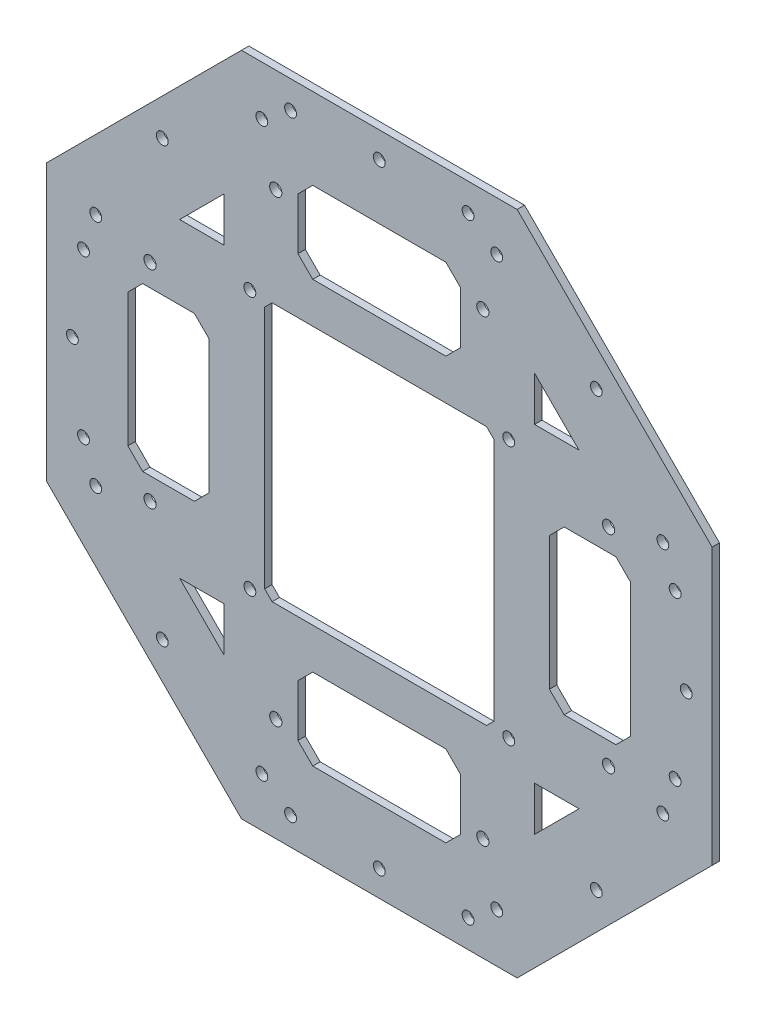
SolidWorks part; units mm, degrees
material "碳纤维板_1600kg_m3"
ref_plane "前视基准面" through (0, 0, 0) normal (0, 0, 1) x (1, 0, 0)
ref_plane "上视基准面" through (0, 0, 0) normal (0, 1, 0) x (1, 0, 0)
ref_plane "右视基准面" through (0, 0, 0) normal (1, 0, 0) x (0, 0, -1)
other "Configuration Table"
sketch "草图1" plane through (0, 0, 0) normal (0, 0, 1) x (1, 0, 0)
  line L0 (90, 37.2792) -> (37.2792, 90)
  line L1 (37.2792, 90) -> (-37.2792, 90)
  line L2 (-37.2792, 90) -> (-90, 37.2792)
  line L3 (-90, 37.2792) -> (-90, -37.2792)
  line L4 (-90, -37.2792) -> (-37.2792, -90)
  line L5 (-37.2792, -90) -> (37.2792, -90)
  line L6 (37.2792, -90) -> (90, -37.2792)
  line L7 (90, -37.2792) -> (90, 37.2792)
  circle A0 centre (83, 0) radius 1.6
  circle A1 centre (76.682, 31.7627) radius 1.6
  circle A2 centre (58.6899, 58.6899) radius 1.6
  circle A3 centre (31.7627, 76.682) radius 1.6
  circle A4 centre (0, 83) radius 1.6
  circle A5 centre (-31.7627, 76.682) radius 1.6
  circle A6 centre (-58.6899, 58.6899) radius 1.6
  circle A7 centre (-76.682, 31.7627) radius 1.6
  circle A8 centre (-83, 0) radius 1.6
  circle A9 centre (-76.682, -31.7627) radius 1.6
  circle A10 centre (-58.6899, -58.6899) radius 1.6
  circle A11 centre (-31.7627, -76.682) radius 1.6
  circle A12 centre (0, -83) radius 1.6
  circle A13 centre (31.7627, -76.682) radius 1.6
  circle A14 centre (58.6899, -58.6899) radius 1.6
  circle A15 centre (76.682, -31.7627) radius 1.6
  circle A16 centre (-35, -35) radius 1.6
  circle A17 centre (-35, 35) radius 1.6
  circle A18 centre (35, -35) radius 1.6
  circle A19 centre (35, 35) radius 1.6
  circle A20 centre (-24, -82.5) radius 1.6
  circle A21 centre (-24, 82.5) radius 1.6
  circle A22 centre (24, -82.5) radius 1.6
  circle A23 centre (24, 82.5) radius 1.6
extrude "正八边形下板_外围16孔_无支脚孔" add sketch "草图1" along normal blind 2
sketch "草图2" plane through (0, 0, 0) normal (0, 0, 1) x (1, 0, 0)
  circle A0 centre (-80, -22) radius 1.6
  circle A1 centre (-80, 22) radius 1.6
  circle A2 centre (80, -22) radius 1.6
  circle A3 centre (80, 22) radius 1.6
extrude "左右摄像头铰链M3孔" cut sketch "草图2" along normal blind 2
sketch "草图3" plane through (0, 0, 0) normal (0, 0, 1) x (1, 0, 0)
  line L0 (24, 9.9411) -> (9.9411, 24)
  line L1 (9.9411, 24) -> (-9.9411, 24)
  line L2 (-9.9411, 24) -> (-24, 9.9411)
  line L3 (-24, 9.9411) -> (-24, -9.9411)
  line L4 (-24, -9.9411) -> (-9.9411, -24)
  line L5 (-9.9411, -24) -> (9.9411, -24)
  line L6 (9.9411, -24) -> (24, -9.9411)
  line L7 (24, -9.9411) -> (24, 9.9411)
  line L8 (-18, 46) -> (18, 46)
  line L9 (18, 46) -> (22, 50)
  line L10 (22, 50) -> (22, 64)
  line L11 (22, 64) -> (18, 68)
  line L12 (18, 68) -> (-18, 68)
  line L13 (-18, 68) -> (-22, 64)
  line L14 (-22, 64) -> (-22, 50)
  line L15 (-22, 50) -> (-18, 46)
  line L16 (-46, -18) -> (-46, 18)
  line L17 (-46, 18) -> (-50, 22)
  line L18 (-50, 22) -> (-64, 22)
  line L19 (-64, 22) -> (-68, 18)
  line L20 (-68, 18) -> (-68, -18)
  line L21 (-68, -18) -> (-64, -22)
  line L22 (-64, -22) -> (-50, -22)
  line L23 (-50, -22) -> (-46, -18)
  line L24 (18, -46) -> (-18, -46)
  line L25 (-18, -46) -> (-22, -50)
  line L26 (-22, -50) -> (-22, -64)
  line L27 (-22, -64) -> (-18, -68)
  line L28 (-18, -68) -> (18, -68)
  line L29 (18, -68) -> (22, -64)
  line L30 (22, -64) -> (22, -50)
  line L31 (22, -50) -> (18, -46)
  line L32 (46, 18) -> (46, -18)
  line L33 (46, -18) -> (50, -22)
  line L34 (50, -22) -> (64, -22)
  line L35 (64, -22) -> (68, -18)
  line L36 (68, -18) -> (68, 18)
  line L37 (68, 18) -> (64, 22)
  line L38 (64, 22) -> (50, 22)
  line L39 (50, 22) -> (46, 18)
  line L40 (-42, -42) -> (-54, -42)
  line L41 (-54, -42) -> (-42, -54)
  line L42 (-42, -54) -> (-42, -42)
  line L43 (-42, 42) -> (-54, 42)
  line L44 (-54, 42) -> (-42, 54)
  line L45 (-42, 54) -> (-42, 42)
  line L46 (42, -42) -> (54, -42)
  line L47 (54, -42) -> (42, -54)
  line L48 (42, -54) -> (42, -42)
  line L49 (42, 42) -> (54, 42)
  line L50 (54, 42) -> (42, 54)
  line L51 (42, 54) -> (42, 42)
extrude "底板几何镂空_中央八边形_四向窗_角窗" cut sketch "草图3" along normal blind 2
sketch "草图4" plane through (0, 0, 0) normal (0, 0, 1) x (1, 0, 0)
  circle A0 centre (-28, -62) radius 1.65
  circle A1 centre (-62, -28) radius 1.65
  circle A2 centre (28, -62) radius 1.65
  circle A3 centre (-62, 28) radius 1.65
  circle A4 centre (-28, 62) radius 1.65
  circle A5 centre (62, -28) radius 1.65
  circle A6 centre (28, 62) radius 1.65
  circle A7 centre (62, 28) radius 1.65
extrude "四向侧支脚上角座8xM3" cut sketch "草图4" along normal blind 2
sketch "飞控托板安装孔垂直投影_参考" plane through (0, 0, 0) normal (0, 0, 1) x (1, 0, 0)
  circle A0 centre (27, 30) radius 1.65 construction
  circle A1 centre (27, -30) radius 1.65 construction
  circle A2 centre (-27, 30) radius 1.65 construction
  circle A3 centre (-27, -30) radius 1.65 construction
sketch "草图6" plane through (0, 0, 0) normal (0, 0, 1) x (1, 0, 0)
  line L8 (-29, -35) -> (29, -35)
  line L9 (29, -35) -> (31, -33)
  line L10 (31, -33) -> (31, 33)
  line L11 (31, 33) -> (29, 35)
  line L12 (29, 35) -> (-29, 35)
  line L13 (-29, 35) -> (-31, 33)
  line L14 (-31, 33) -> (-31, -33)
  line L15 (-31, -33) -> (-29, -35)
extrude "飞控螺丝检修口_62x70" cut sketch "草图6" along normal blind 2
